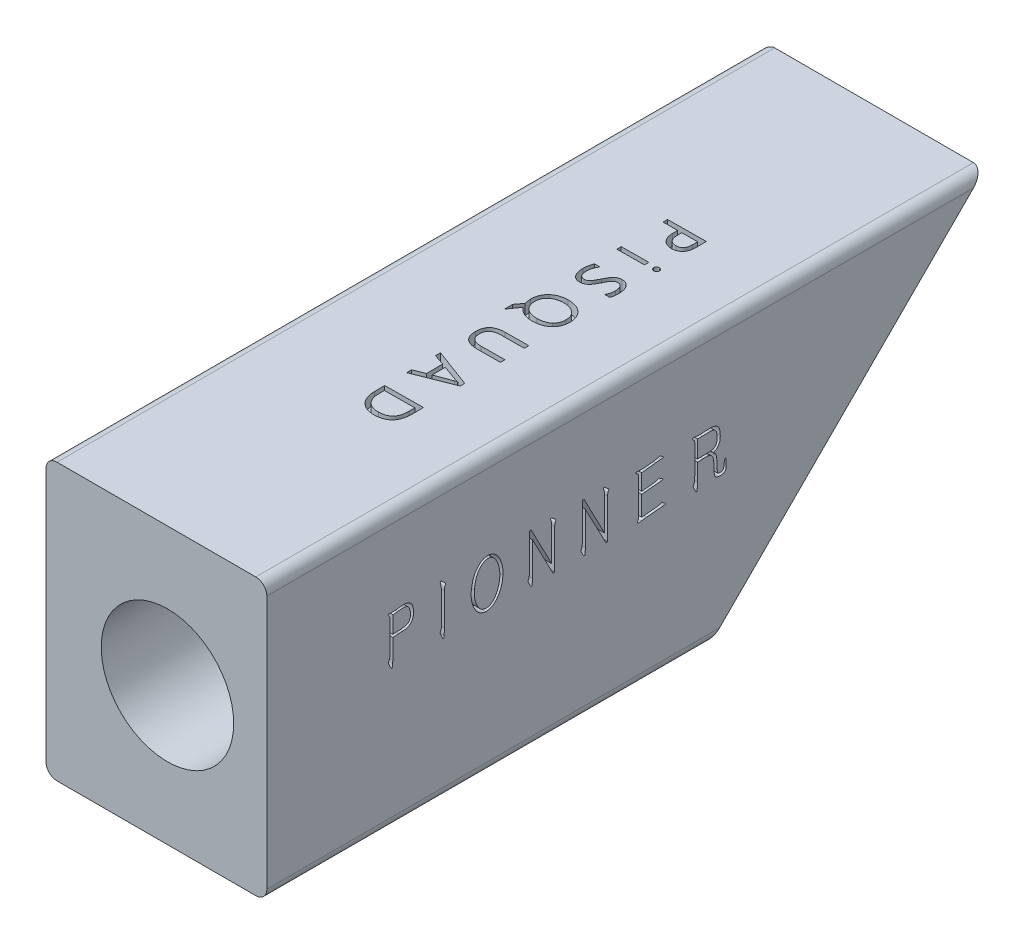
SolidWorks part; units mm, degrees
ref_plane "前视基准面" through (0, 0, 0) normal (0, 0, 1) x (1, 0, 0)
ref_plane "上视基准面" through (0, 0, 0) normal (0, 1, 0) x (1, 0, 0)
ref_plane "右视基准面" through (0, 0, 0) normal (1, 0, 0) x (0, 0, -1)
other "Configuration Table"
sketch "Sketch1" plane through (0, 0, 0) normal (1, 0, 0) x (0, 0, -1)
  line L0 (20, -12.5) -> (45, 12.5)
  line L1 (-20, -12.5) -> (20, -12.5)
  line L2 (-20, -12.5) -> (-20, 12.5)
  line L3 (-20, 12.5) -> (20, 12.5)
  line L4 (20, -12.5) -> (20, 12.5)
  line L5 (-20, -12.5) -> (20, 12.5) construction
  line L6 (-20, 12.5) -> (20, -12.5) construction
  line L7 (20, 12.5) -> (45, 12.5)
  point P0 (0, 0)
  dimension "D1" = 25
  dimension "D2" = 40
  dimension "D3" = 45
extrude "Boss-Extrude1" add sketch "Sketch1" along normal blind 20 contours L7 L4 L0 | L1 L4 L3 L2
sketch "Sketch2" plane through (0, 0, 0) normal (0, 0, 1) x (1, 0, 0)
  line L0 (10, 12.5) -> (10, -12.5) construction
  line L1 (20, 12.5) -> (0, 12.5) construction
  line L2 (20, -12.5) -> (0, -12.5) construction
  line L3 (0, 0) -> (20, 0) construction
  line L4 (20, -12.5) -> (20, 12.5) construction
  circle A0 centre (11, 0) radius 6
  dimension "D1" = 9
extrude "Cut-Extrude1" cut sketch "Sketch2" against normal blind 67 and the other way blind 43
fillet "Fillet1" radius 1 4 edges at (0, 12.5, -12.5) (0, -12.5, 0) (20, -12.5, 0) (20, 12.5, -12.5)
sketch "Sketch4" plane through (0, 0, 0) normal (-1, 0, 0) x (0, 0, 1)
  circle A0 centre (0, 0) radius 11
extrude "Cut-Extrude2" cut sketch "Sketch4" against normal blind 2
sketch "Sketch5" plane through (0, 12.5, 0) normal (0, 1, 0) x (1, 0, 0)
  line L0 (9.4482, 45) -> (10, -20) construction
  line L1 (19, 45) -> (1, 45) construction
  line L2 (19, -20) -> (1, -20) construction
  text T0 "PiSQUAD" font "Segoe UI" height 3.5
extrude "Cut-Extrude3" cut sketch "Sketch5" against normal blind 1
sketch "Sketch6" plane through (20, 0, 0) normal (1, 0, 0) x (0, 0, -1)
  line L0 (-20, 0) -> (32.5, 0) construction
  line L1 (-20, -11.5) -> (-20, 11.5) construction
  line L2 (21, -11.5) -> (44, 11.5) construction
  text T0 "PIONNER" font "汉仪长仿宋体" height in points 18
extrude "Cut-Extrude4" cut sketch "Sketch6" against normal blind 1
